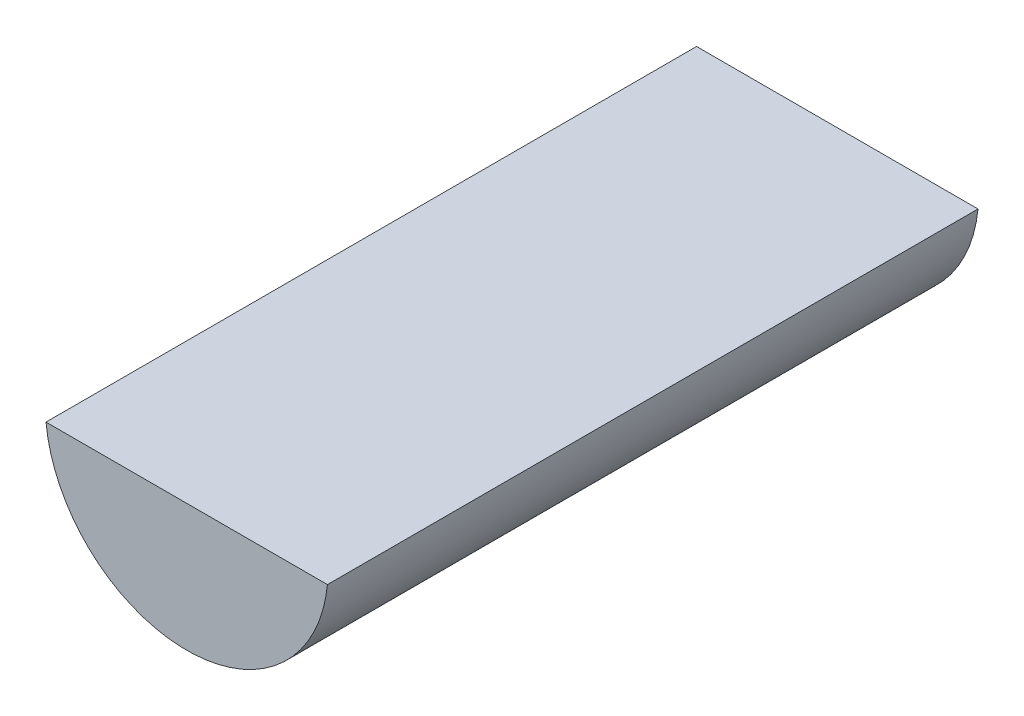
SolidWorks part; units mm, degrees
ref_plane "Front" through (0, 0, 0) normal (0, 0, 1) x (1, 0, 0)
ref_plane "Top" through (0, 0, 0) normal (0, 1, 0) x (1, 0, 0)
ref_plane "Right" through (0, 0, 0) normal (1, 0, 0) x (0, 0, -1)
sketch "Sketch1" plane through (0, 0, 0) normal (0, 0, 1) x (1, 0, 0)
  line L0 (-49.7494, -5) -> (49.7494, -5)
  line L1 (0, -50) -> (0, -5) construction
  arc A0 (-49.7494, -5) -> (49.7494, -5) centre (0, 0) ccw
  dimension "D1" = 100
  dimension "D2" = 45
extrude "Boss-Extrude1" add sketch "Sketch1" along normal blind 230
